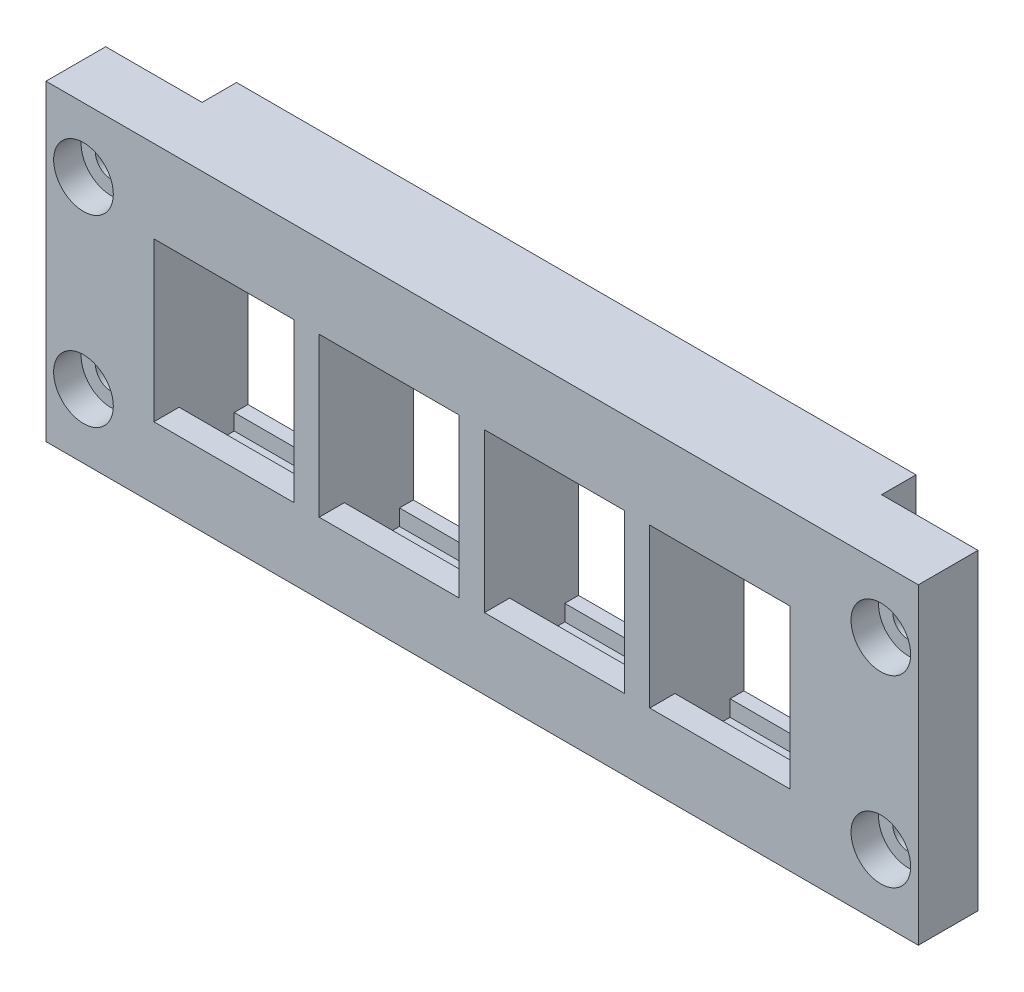
SolidWorks part; units mm, degrees
ref_plane "Front Plane" through (0, 0, 0) normal (0, 0, 1) x (1, 0, 0)
ref_plane "Top Plane" through (0, 0, 0) normal (0, 1, 0) x (1, 0, 0)
ref_plane "Right Plane" through (0, 0, 0) normal (1, 0, 0) x (0, 0, -1)
sketch "Sketch1" plane through (0, 0, 0) normal (0, 0, 1) x (1, 0, 0)
  line L1 (-47.5, 17) -> (47.5, 17)
  line L2 (-47.5, 17) -> (-47.5, -17)
  line L3 (-47.5, -17) -> (47.5, -17)
  line L4 (47.5, 17) -> (47.5, -17)
  line L5 (-47.5, 17) -> (47.5, -17) construction
  line L6 (-47.5, -17) -> (47.5, 17) construction
  point P0 (0, 0)
  dimension "D1" = 95
  dimension "D2" = 34
extrude "Boss-Extrude1" add sketch "Sketch1" along normal blind 6.5
sketch "Sketch2" plane through (0, 0, 0) normal (0, 0, -1) x (-1, 0, 0)
  line L0 (47.5, -17) -> (-47.5, -17) construction
  line L1 (-37, -17) -> (37, -17)
  line L2 (-37, -17) -> (-37, 17)
  line L3 (-37, 17) -> (37, 17)
  line L4 (37, -17) -> (37, 17)
  line L5 (-47.5, 17) -> (47.5, 17) construction
  point P6 (0, 17)
  dimension "D1" = 74
extrude "Boss-Extrude2" add sketch "Sketch2" along normal blind 3.75
sketch "Sketch6" plane through (0, 0, 6.5) normal (0, 0, 1) x (1, 0, 0)
  point P0 (-43.42, 10)
  point P2 (-43.42, -10)
  point P4 (43.42, 10)
  point P6 (43.42, -10)
  dimension "D1" = 20
  dimension "D2" = 43.42
  dimension "D3" = 43.42
  dimension "D4" = 10
hole_wizard "CBORE for M3 SHCS1" positions "Sketch6" profile "Sketch5" counterbore size "M3" standard "ANSI Metric"
sketch "Sketch5" plane through (-43.42, 10, 6.5) normal (1, 0, 0) x (0, -1, 0)
  line L0 (0, 0) -> (0, 11.1215)
  line L1 (0, 11.1215) -> (1.7, 10.1)
  line L2 (1.7, 10.1) -> (1.7, 3)
  line L3 (1.7, 3) -> (3.25, 3)
  line L4 (3.25, 3) -> (3.25, 0)
  line L5 (3.25, 0) -> (0, 0)
  line L10 (0, 11.1215) -> (-1.7, 10.1) construction
  line L11 (0, -6.35) -> (0, 107.95) construction
  dimension "Hole Dia." = 3.4
  dimension "Hole Depth" = 10.1
  dimension "C'Bore Dia." = 6.5
  dimension "C'Bore Depth" = 3
  dimension "Drill Angle" = 118
ref_plane "Plane1" through (33.5, 0, 0) normal (1, 0, 0) x (0, 0, -1)
sketch "Sketch7" plane through (33.5, 0, 0) normal (1, 0, 0) x (0, 0, -1)
  line L0 (-5.7534, 23.5034) -> (-5.7534, 7.5034) construction
  line L1 (-5.7534, 7.5034) -> (0.7466, 7.5034) construction
  line L2 (2.2466, 7.5034) -> (2.2466, 9.0034) construction
  line L3 (4.2466, -12.9966) -> (8.1247, -12.9966) construction
  line L4 (2.2466, 9.0034) -> (0.7466, 7.5034) construction
  line L5 (2.2466, 7.5034) -> (3.7466, 7.5034) construction
  line L6 (4.2466, 7.5034) -> (4.2466, 23.5034) construction
  line L7 (2.2466, -11.4966) -> (8.1247, -11.4966) construction
  line L8 (-5.7534, 23.5034) -> (4.2466, 23.5034) construction
  line L9 (-5.7534, 23.5034) -> (2.2466, 23.5034) construction
  line L10 (-5.7534, 7.5034) -> (2.2466, 7.5034) construction
  line L11 (-0.7534, -12.9966) -> (2.2466, -11.4966) construction
  line L12 (-0.7534, -12.9966) -> (2.2466, -13.9966) construction
  line L13 (2.2466, -14.4966) -> (2.2466, -12.7466) construction
  line L14 (-0.7534, -11.4966) -> (-8.75, -11.4966) construction
  line L15 (-0.7534, -12.9966) -> (-8.75, -12.9966) construction
  line L16 (8.1247, -11.4966) -> (8.1247, -12.9966) construction
  line L19 (-6.5034, 8.0068) -> (-3.7568, 8.0068) construction
  line L22 (2.2466, 7.5034) -> (2.2466, 9.0034) construction
  line L23 (2.2466, 9.0034) -> (-3.7568, 9.0034) construction
  line L27 (-3.7568, 11.0034) -> (-3.7568, 16.0034) construction
  line L33 (-5.7534, 15.5034) -> (4.2466, 15.3434) construction
  line L47 (2.2466, -14.4966) -> (-3.7568, -14.4966) construction
  line L51 (-3.7568, -16.4966) -> (3.7466, -16.4966) construction
  line L53 (-3.7568, -16.4966) -> (-3.7568, -21.4966) construction
  line L59 (-3.7568, 11.0034) -> (3.7466, 11.0034) construction
  line L60 (-6.5034, 16.0034) -> (-3.7568, 16.0034) construction
  line L61 (-6.5034, -21.4966) -> (-3.7568, -21.4966) construction
  line L64 (-3.7568, -9.25) -> (-3.7568, -14.4966) construction
  line L65 (-3.7568, 8.0068) -> (-3.7568, 9.0034) construction
  line L69 (3.7466, -12.7466) -> (2.2466, -12.7466) construction
  line L70 (3.7466, -16.4966) -> (3.7466, -12.7466) construction
  line L71 (3.7466, -14.4966) -> (3.7466, -12.7466) construction
  line L72 (3.7466, 7.5034) -> (3.7466, 11.0034) construction
  line L73 (3.7466, 7.5034) -> (3.7466, 9.0034) construction
  line L74 (-6.5034, -9.25) -> (-3.7568, -9.25) construction
  line L75 (-6.5034, -9.25) -> (-6.5034, -21.4966) construction
  line L76 (-6.5034, 8.0068) -> (-6.5034, 16.0034) construction
  line L77 (-6.5034, 8.0068) -> (-3.7568, 8.0068)
  line L78 (-3.7568, 8.0068) -> (-3.7568, 9.0034)
  line L79 (-3.7568, 9.0034) -> (2.2466, 9.0034)
  line L80 (2.2466, 9.0034) -> (2.2466, 7.5034)
  line L81 (2.2466, 7.5034) -> (3.7466, 7.5034)
  line L83 (3.7466, -12.7466) -> (2.2466, -12.7466)
  line L84 (2.2466, -12.7466) -> (2.2466, -14.4966)
  line L85 (2.2466, -14.4966) -> (-3.7568, -14.4966)
  line L86 (-3.7568, -14.4966) -> (-3.7568, -9.25)
  line L87 (-3.7568, -9.25) -> (-6.5034, -9.25)
  line L88 (-6.5034, -9.25) -> (-6.5034, 8.0068)
  line L89 (3.7466, 7.5034) -> (6.3555, 7.5034)
  line L90 (6.3555, 7.5034) -> (6.3555, -12.7466)
  line L91 (6.3555, -12.7466) -> (3.8711, -12.7466)
  line L92 (3.8711, -12.7466) -> (3.7466, -12.7466)
  dimension "D1" = 27.5
  dimension "D2" = 5
  dimension "D3" = 1.5
  dimension "D4" = 16
  dimension "D5" = 1.5
  dimension "D6" = 6.5
  dimension "D7" = 10
  dimension "D8" = 5
extrude "Cut-Extrude1" cut sketch "Sketch7" against normal blind 15.25
pattern_linear "LPattern1" count 4 spacing 18 along (-1, 0, 0) of "Cut-Extrude1"
